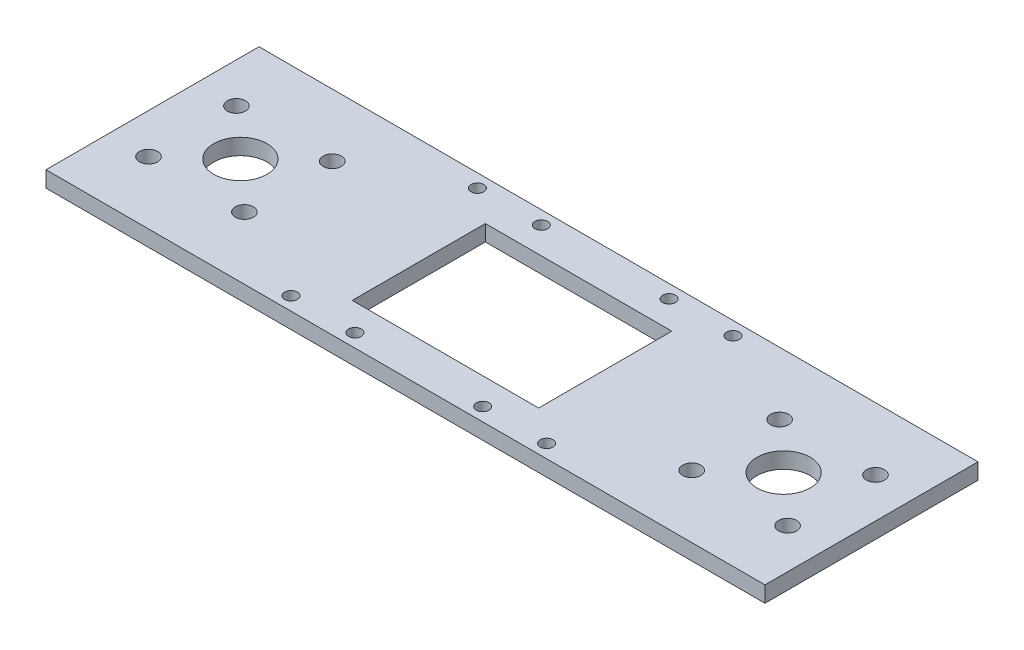
SolidWorks part; units mm, degrees
ref_plane "Front Plane" through (0, 0, 0) normal (0, 0, 1) x (1, 0, 0)
ref_plane "Top Plane" through (0, 0, 0) normal (0, 1, 0) x (1, 0, 0)
ref_plane "Right Plane" through (0, 0, 0) normal (1, 0, 0) x (0, 0, -1)
sketch "Sketch1" plane through (0, 0, 0) normal (0, 1, 0) x (1, 0, 0)
  line L0 (0, 0) -> (0, -14.43) construction
  line L1 (-67.5, 20) -> (67.5, 20)
  line L2 (-67.5, 20) -> (-67.5, -20)
  line L3 (-67.5, -20) -> (67.5, -20)
  line L4 (67.5, 20) -> (67.5, -20)
  line L5 (-67.5, 20) -> (67.5, -20) construction
  line L6 (-67.5, -20) -> (67.5, 20) construction
  line L7 (0, 0) -> (6.9805, 0) construction
  line L8 (-5, 10) -> (5, 10)
  line L9 (-5, 10) -> (-5, -10)
  line L10 (-5, -10) -> (5, -10)
  line L11 (5, 10) -> (5, -10)
  line L12 (-5, 10) -> (5, -10) construction
  line L13 (-5, -10) -> (5, 10) construction
  line L14 (0, 20) -> (0, -20) construction
  circle A0 centre (-51, 0) radius 5
  circle A1 centre (-60, 8.25) radius 1.7
  circle A2 centre (-42, 8.25) radius 1.7
  circle A3 centre (-42, -8.25) radius 1.7
  circle A4 centre (-60, -8.25) radius 1.7
  circle A26 centre (51, 0) radius 5
  circle A27 centre (42, 8.25) radius 1.7
  circle A28 centre (42, -8.25) radius 1.7
  circle A29 centre (60, -8.25) radius 1.7
  circle A30 centre (60, 8.25) radius 1.7
  point P0 (0, 0)
  dimension "D3" = 10
  dimension "D4" = 16.5
  dimension "D5" = 20
  dimension "D6" = 11.75
  dimension "D9" = 10
  dimension "D11" = 7.5
  dimension "D12" = 10
  dimension "D13" = 11.75
  dimension "D10" = 16.5
  dimension "D17" = 18
  dimension "D1" = 135
  dimension "D2" = 40
  dimension "D7" = 2
  dimension "D8" = 2
extrude "Boss-Extrude1" add sketch "Sketch1" along normal blind 3
sketch "Sketch3" plane through (0, 3, 0) normal (0, 1, 0) x (1, 0, 0)
  line L4 (-5, 10) -> (-5, -10) construction
  line L6 (67.5, 20) -> (-67.5, 20) construction
  line L10 (0, 0) -> (0, 13.8836) construction
  circle A1 centre (-12, 17.5) radius 1.2
  circle A2 centre (-12, -17.5) radius 1.2
  circle A4 centre (-24, 17.5) radius 1.2
  circle A5 centre (-24, -17.5) radius 1.2
  circle A8 centre (24, -17.5) radius 1.2
  circle A9 centre (24, 17.5) radius 1.2
  circle A10 centre (12, -17.5) radius 1.2
  circle A11 centre (12, 17.5) radius 1.2
  dimension "D1" = 2.5
  dimension "D2" = 7
  dimension "D3" = 35
  dimension "D5" = 2
  dimension "D6" = 2.4
  dimension "D7" = 2.4
  dimension "D8" = 12
  dimension "D4" = 7
extrude "Cut-Extrude1" cut sketch "Sketch3" against normal through all
sketch "Sketch4" plane through (0, 3, 0) normal (0, 1, 0) x (1, 0, 0)
  line L1 (-17.5, 12.5) -> (17.5, 12.5)
  line L2 (-17.5, 12.5) -> (-17.5, -12.5)
  line L3 (-17.5, -12.5) -> (17.5, -12.5)
  line L4 (17.5, 12.5) -> (17.5, -12.5)
  line L5 (-17.5, 12.5) -> (17.5, -12.5) construction
  line L6 (-17.5, -12.5) -> (17.5, 12.5) construction
  point P0 (0, 0)
  dimension "D1" = 35
  dimension "D2" = 25
extrude "Cut-Extrude2" cut sketch "Sketch4" against normal through all
